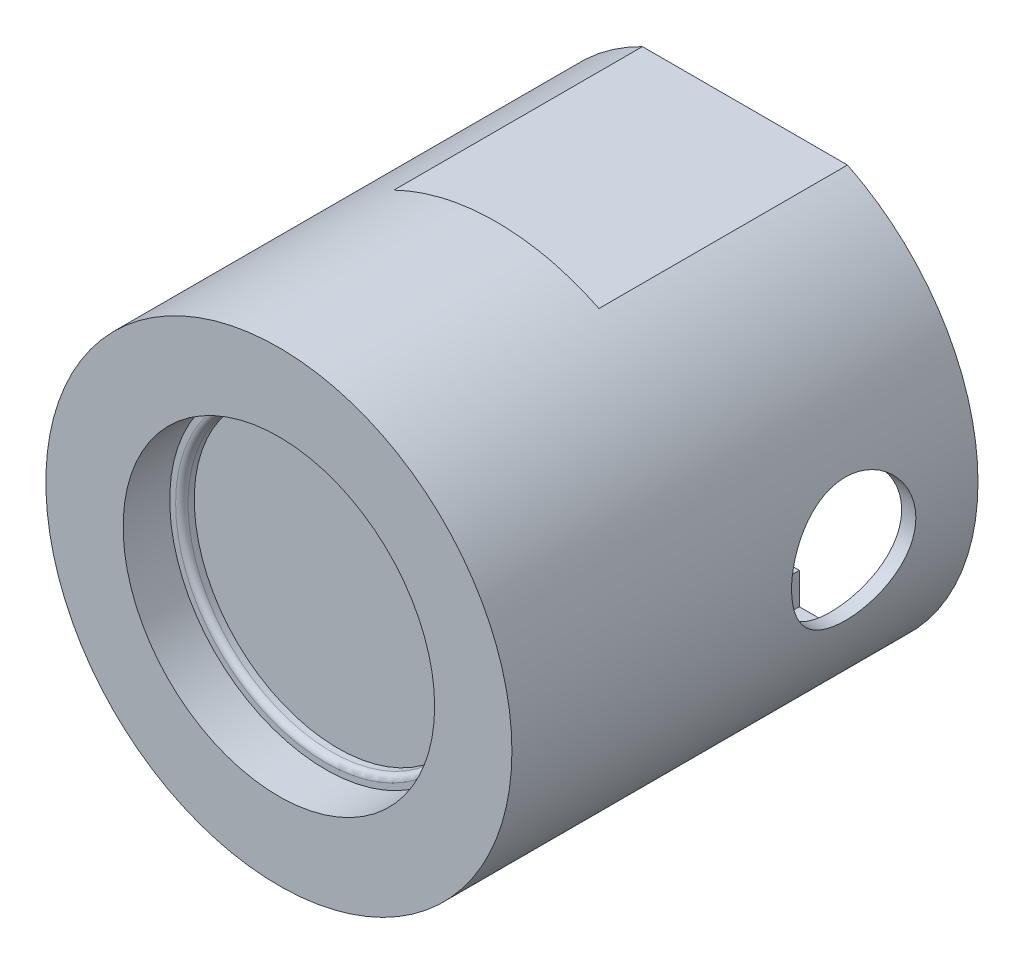
SolidWorks part; units mm, degrees
ref_plane "Front Plane" through (0, 0, 0) normal (0, 0, 1) x (1, 0, 0)
ref_plane "Top Plane" through (0, 0, 0) normal (0, 1, 0) x (1, 0, 0)
ref_plane "Right Plane" through (0, 0, 0) normal (1, 0, 0) x (0, 0, -1)
sketch "Sketch3" plane through (0, 0, 0) normal (0, 0, 1) x (1, 0, 0)
  circle A0 centre (0, 0) radius 19.05
  dimension "D1" = 38.1
extrude "Boss-Extrude1" add sketch "Sketch3" against normal blind 38.1
sketch "Sketch6" plane through (0, 0, -38.1) normal (0, 0, -1) x (-1, 0, 0)
  line L0 (0, 0) -> (0, 15.8437) construction
  line L1 (0, 0) -> (-17.6041, 0) construction
  line L2 (4.4457, 13.5556) -> (-4.4457, 13.5556)
  line L3 (-4.4457, 13.5556) -> (-4.4457, 16.1314)
  line L4 (-4.4457, 16.1314) -> (-7.7354, 16.1314)
  line L7 (4.4457, 13.5556) -> (4.4457, 16.1314)
  line L8 (4.4457, 16.1314) -> (7.7354, 16.1314)
  line L10 (-4.4457, -16.1314) -> (-7.7354, -16.1314)
  line L11 (-4.4457, -13.5556) -> (-4.4457, -16.1314)
  line L12 (4.4457, -13.5556) -> (-4.4457, -13.5556)
  line L13 (4.4457, -13.5556) -> (4.4457, -16.1314)
  line L14 (4.4457, -16.1314) -> (7.7354, -16.1314)
  arc A0 (-7.7354, 16.1314) -> (-7.7354, -16.1314) centre (0, 0) ccw
  arc A1 (7.7354, 16.1314) -> (7.7354, -16.1314) centre (0, 0) cw
  point P11 (0, 13.5556)
extrude "Cut-Extrude2" cut sketch "Sketch6" against normal blind 25.4 contours A0 L10 L11 L12 L13 L14 A1 L8 L7 L2 L3 L4
sketch "Sketch10" plane through (0, 0, -38.1) normal (0, 0, -1) x (-1, 0, 0)
  line L0 (-8.382, 17.1069) -> (8.382, 17.1069)
  line L1 (0, 0) -> (-17.3717, 0) construction
  line L2 (-8.382, -17.1069) -> (8.382, -17.1069)
  circle A0 centre (0, 0) radius 19.05 construction
  arc A1 (-8.382, 17.1069) -> (8.382, 17.1069) centre (0, 0.04) cw
  arc A2 (-8.382, -17.1069) -> (8.382, -17.1069) centre (0, -0.04) ccw
  dimension "D1" = 16.764
extrude "Cut-Extrude4" cut sketch "Sketch10" against normal blind 20.32
sketch "Sketch11" plane through (0, 0, 0) normal (0, 0, 1) x (1, 0, 0)
  circle A0 centre (0, 0) radius 12.7325
extrude "Cut-Extrude5" cut sketch "Sketch11" against normal blind 3.81
sketch "Sketch12" plane through (0, 0, -3.81) normal (0, 0, 1) x (1, 0, 0)
  circle A0 centre (0, 0) radius 11.7429
extrude "Cut-Extrude6" cut sketch "Sketch12" against normal blind 1.016
fillet "Fillet2" radius 0.508 1 edges at (11.7429, 0, -3.81)
sketch "Sketch14" plane through (0, 0, 0) normal (1, 0, 0) x (0, 0, -1)
  line L0 (38.1, 0) -> (27.94, 0) construction
  line L1 (38.1, -17.1069) -> (38.1, 17.1069) construction
  line L2 (3.81, 0) -> (38.1, 0) construction
  line L3 (3.81, 19.05) -> (3.81, -19.05) construction
  circle A0 centre (27.94, 0) radius 5.08
  dimension "D2" = 10.16
  dimension "D1" = 10.16
extrude "Cut-Extrude7" cut sketch "Sketch14" against normal through all both and the other way through all
